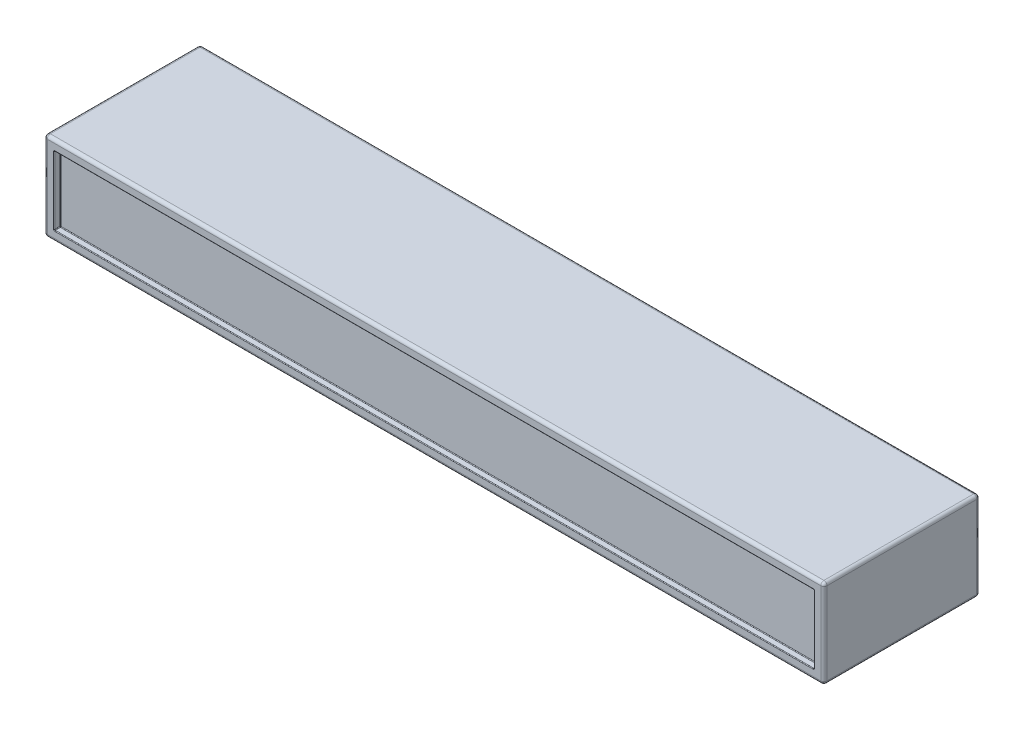
SolidWorks part; units mm, degrees
ref_plane "Front Plane" through (0, 0, 0) normal (0, 0, 1) x (1, 0, 0)
ref_plane "Top Plane" through (0, 0, 0) normal (0, 1, 0) x (1, 0, 0)
ref_plane "Right Plane" through (0, 0, 0) normal (1, 0, 0) x (0, 0, -1)
sketch "Sketch1" plane through (0, 0, 0) normal (0, 0, 1) x (1, 0, 0)
  line L1 (0, 0) -> (2500, 0)
  line L2 (0, 0) -> (0, 284)
  line L3 (0, 284) -> (2500, 284)
  line L4 (2500, 0) -> (2500, 284)
  dimension "D1" = 284
  dimension "D2" = 2500
extrude "Boss-Extrude1" add sketch "Sketch1" along normal blind 500
fillet "Fillet1" radius 10 12 edges at (2500, 142, 0) (2500, 0, 250) (1250, 0, 0) (2500, 284, 250) (1250, 284, 0) (0, 284, 250) (0, 0, 250) (0, 142, 0) (1250, 284, 500) (2500, 142, 500) (1250, 0, 500) (0, 142, 500)
sketch "Sketch2" plane through (0, 0, 500) normal (0, 0, 1) x (1, 0, 0)
  line L0 (2490, 0) -> (10, 0) construction
  line L1 (2468, 252) -> (32, 252)
  line L2 (2468, 252) -> (2468, 32)
  line L3 (2468, 32) -> (32, 32)
  line L4 (32, 252) -> (32, 32)
  line L5 (10, 284) -> (2490, 284) construction
  line L6 (2500, 274) -> (2500, 10) construction
  line L7 (0, 10) -> (0, 274) construction
  dimension "D1" = 32
  dimension "D2" = 32
  dimension "D3" = 32
  dimension "D4" = 32
extrude "Cut-Extrude1" cut sketch "Sketch2" against normal blind 20
fillet "Fillet2" radius 2 12 edges at (2468, 142, 500) (2468, 32, 490) (1250, 32, 500) (32, 32, 490) (32, 142, 500) (2468, 252, 490) (32, 252, 490) (1250, 252, 500) (1250, 32, 480) (32, 142, 480) (1250, 252, 480) (2468, 142, 480)
